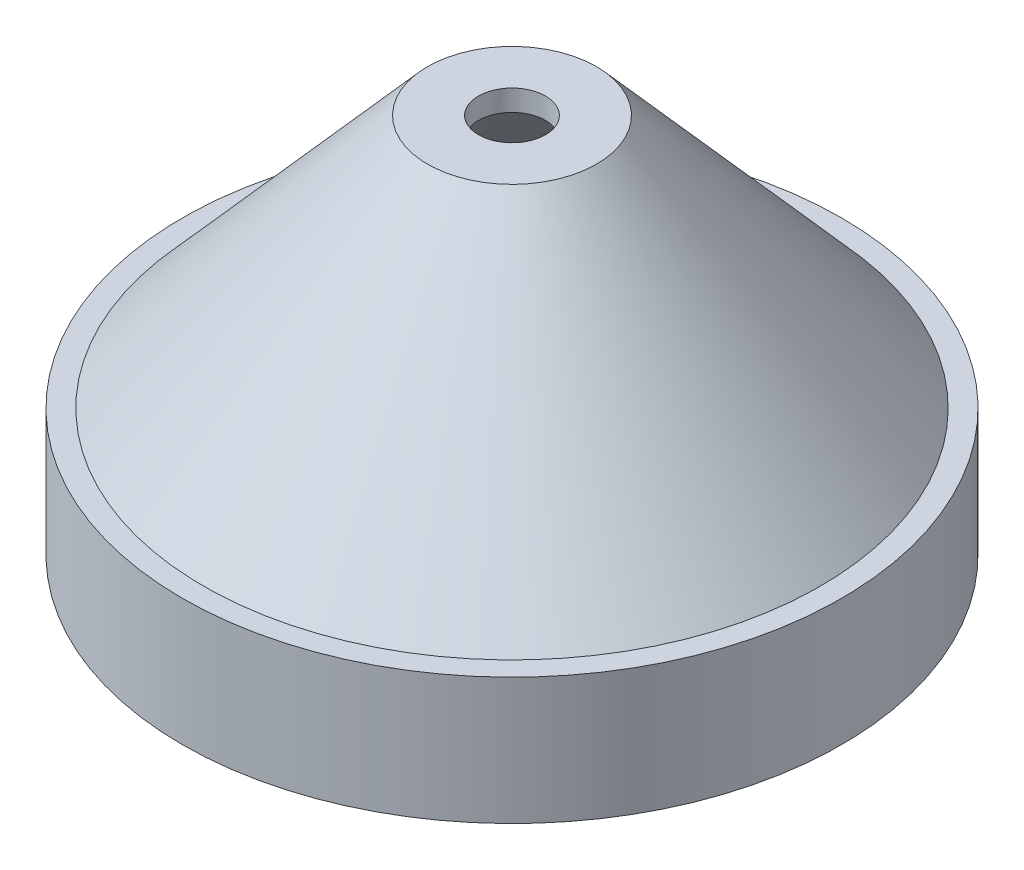
SolidWorks part; units mm, degrees
material "6061-T6 (SS)"
ref_plane "Front Plane" through (0, 0, 0) normal (0, 0, 1) x (1, 0, 0)
ref_plane "Top Plane" through (0, 0, 0) normal (0, 1, 0) x (1, 0, 0)
ref_plane "Right Plane" through (0, 0, 0) normal (1, 0, 0) x (0, 0, -1)
sketch "Sketch1" plane through (0, 0, 0) normal (0, 1, 0) x (1, 0, 0)
  circle A0 centre (0, 0) radius 49.53
  dimension "D1" = 99.06
extrude "Boss-Extrude1" add sketch "Sketch1" along normal blind 76.2
sketch "Sketch8" plane through (0, 0, 0) normal (0, 0, 1) x (1, 0, 0)
  line L0 (49.53, 19.05) -> (46.355, 19.05)
  line L1 (49.53, 0) -> (49.53, 76.2) construction
  line L2 (46.355, 19.05) -> (12.7, 57.15)
  line L3 (12.7, 57.15) -> (0, 57.15)
  line L4 (0, 57.15) -> (0, 76.2)
  line L5 (49.53, 76.2) -> (-49.53, 76.2) construction
  line L6 (0, 76.2) -> (49.53, 76.2)
  line L7 (49.53, 76.2) -> (49.53, 19.05)
  line L8 (49.53, 19.05) -> (50.0745, 19.1161)
  line L9 (-49.53, 0) -> (49.53, 0) construction
  dimension "D1" = 19.05
  dimension "D2" = 3.175
  dimension "D3" = 12.7
  dimension "D4" = 57.15
ref_axis "Axis1" through (0, 76.2, 0) along (0, -1, 0)
revolve "Cut-Revolve1" cut sketch "Sketch8" angle 360 about axis through (0, 76.2, 0) along (0, -1, 0)
shell "Shell1" thickness 3.175
hole_wizard "3/8 Clearance Hole1" positions "Sketch10" profile "Sketch9" hole size "3/8" standard "ANSI Inch"
sketch "Sketch10" plane through (0, 57.15, 0) normal (0, 1, 0) x (1, 0, 0)
  point P0 (0, 0)
sketch "Sketch9" plane through (0, 57.15, 0) normal (1, 0, 0) x (0, 0, 1)
  line L0 (0, 0) -> (0, 28.4295)
  line L1 (0, 28.4295) -> (5.0419, 25.4)
  line L2 (5.0419, 25.4) -> (5.0419, 0)
  line L5 (5.0419, 0) -> (0, 0)
  line L10 (0, 28.4295) -> (-5.0419, 25.4) construction
  line L11 (0, -6.35) -> (0, 107.95) construction
  dimension "Hole Dia." = 10.0838
  dimension "Hole Depth" = 25.4
  dimension "Drill Angle" = 118
